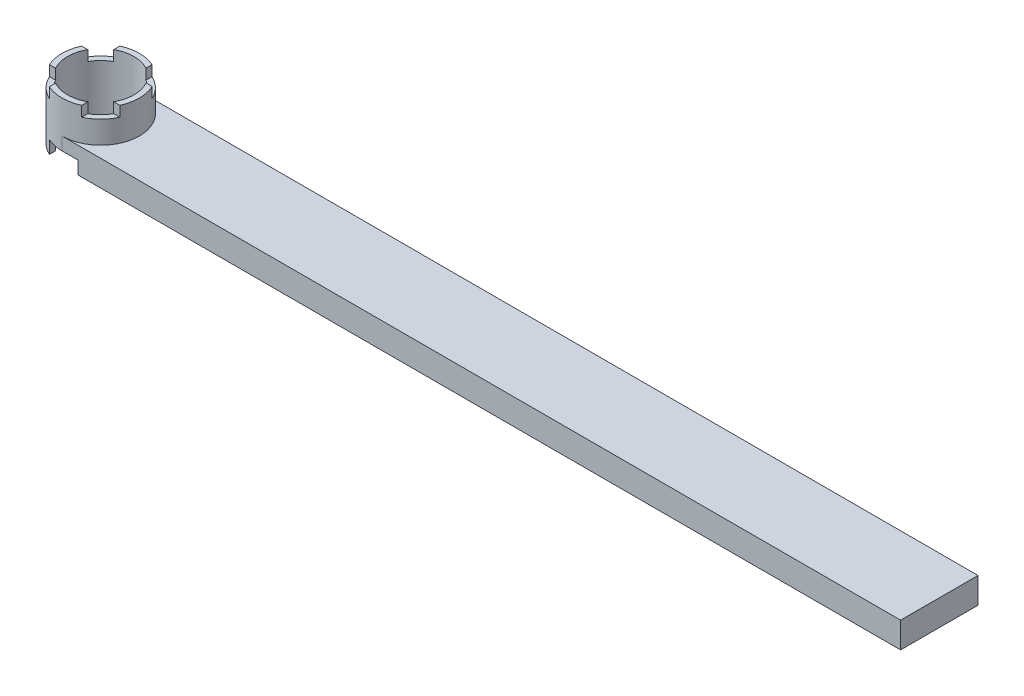
SolidWorks part; units mm, degrees
ref_plane "前视基准面" through (0, 0, 0) normal (0, 0, 1) x (1, 0, 0)
ref_plane "上视基准面" through (0, 0, 0) normal (0, 1, 0) x (1, 0, 0)
ref_plane "右视基准面" through (0, 0, 0) normal (1, 0, 0) x (0, 0, -1)
other "Configuration Table"
sketch "草图1" plane through (0, 0, 0) normal (0, 1, 0) x (1, 0, 0)
  line L1 (0, 6) -> (130, 6)
  line L3 (0, -6) -> (130, -6)
  line L4 (130, 6) -> (130, -6)
  circle A0 centre (0, 0) radius 5.15
  circle A1 centre (0, 0) radius 6
  dimension "D1" = 10.3
  dimension "D2" = 12
  dimension "D3" = 130
extrude "凸台-拉伸3" add sketch "草图1" along normal blind 4 contours A1 L3 L4 L1 | A1 A0
sketch "草图2" plane through (0, 4, 0) normal (0, 1, 0) x (1, 0, 0)
  circle A0 centre (0, 0) radius 6
  arc A1 (0, 6) -> (0, -6) centre (0, 0) ccw construction
  circle A2 centre (0, 0) radius 5.15
  circle A3 centre (0, 0) radius 5.15 construction
extrude "凸台-拉伸4" add sketch "草图2" along normal blind 3.5 contours A0 | A2
sketch "草图3" plane through (0, 0, 0) normal (0, -1, 0) x (1, 0, 0)
  line L0 (0, 0) -> (0, 5.15) construction
  line L1 (0, 0) -> (-6, 0) construction
  line L2 (-2.5, -8.5) -> (2.5, -8.5)
  line L4 (-6, 2.5) -> (-6, -2.5)
  line L5 (-6, -2.5) -> (-2.5, -2.5)
  line L6 (6, 2.5) -> (6, -2.5)
  line L8 (-2.5, 2.5) -> (-2.5, 8.5)
  line L9 (-2.5, 8.5) -> (2.5, 8.5)
  line L10 (2.5, 2.5) -> (2.5, 8.5)
  line L15 (2.5, -2.5) -> (2.5, -8.5)
  line L17 (-2.5, -2.5) -> (-2.5, -8.5)
  line L19 (2.5, -2.5) -> (6, -2.5)
  line L20 (-6, 2.5) -> (-2.5, 2.5)
  line L21 (6, 2.5) -> (2.5, 2.5)
  circle A0 centre (0, 0) radius 6
  arc A1 (0, 6) -> (0, -6) centre (0, 0) ccw construction
  dimension "D1" = 6
  dimension "D2" = 6
  dimension "D4" = 2.5
  dimension "D5" = 2.5
  dimension "D6" = 2.5
  dimension "D7" = 6
extrude "切除-拉伸1" cut sketch "草图3" against normal blind 2 contours L21 L10 L9 L8 L20 L4 L5 L17 L2 L15 L19 L6
sketch "草图4" plane through (0, 7.5, 0) normal (0, 1, 0) x (1, 0, 0)
  line L0 (2.5, 2.53) -> (8.5, 2.53)
  line L5 (8.5, 2.53) -> (8.5, -2.5)
  line L6 (8.5, -2.5) -> (2.5, -2.5)
  line L7 (2.5, -2.5) -> (2.5, -8.5)
  line L8 (2.5, -8.5) -> (-2.5, -8.5)
  line L9 (-2.5, -8.5) -> (-2.5, -2.5)
  line L10 (-2.5, -2.5) -> (-8.5, -2.5)
  line L11 (-8.5, -2.5) -> (-8.5, 2.5)
  line L12 (-8.5, 2.5) -> (-2.5, 2.5)
  line L13 (-2.5, 2.5) -> (-2.5, 8.53)
  line L14 (-2.5, 8.53) -> (2.5, 8.53)
  line L15 (2.5, 8.53) -> (2.5, 2.53)
  line L16 (0, 0) -> (6, 0) construction
  line L18 (0, -6) -> (0, 0) construction
  circle M17 centre (0, 0) radius 6
  circle M18 centre (0, 0) radius 5.15
  dimension "D1" = 2.5
  dimension "D2" = 2.5
  dimension "D3" = 2.53
  dimension "D4" = 2.5
  dimension "D5" = 2.5
  dimension "D6" = 2.5
  dimension "D7" = 2.5
  dimension "D8" = 2.5
  dimension "D9" = 6
  dimension "D10" = 6
  dimension "D11" = 6
  dimension "D12" = 6
extrude "凸台-拉伸5" add sketch "草图4" along normal blind 1.6 contours L12 L10 M17 M18 | L15 L13 M17 M18 | L6 L0 M17 M18 | L9 L7 M17 M18
